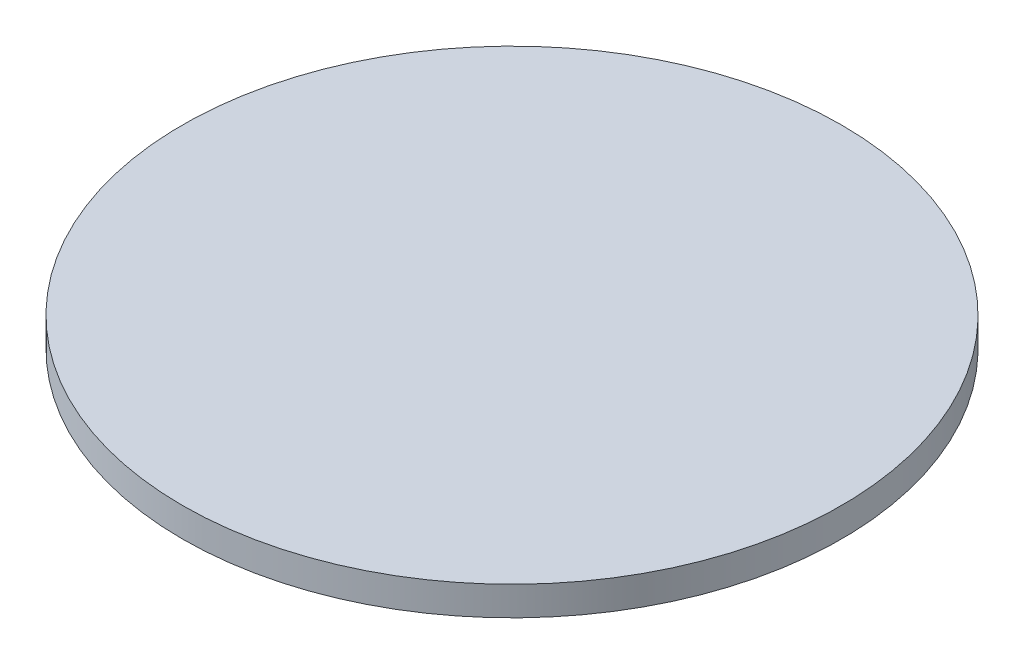
SolidWorks part; units mm, degrees
ref_plane "Front" through (0, 0, 0) normal (0, 0, 1) x (1, 0, 0)
ref_plane "Top" through (0, 0, 0) normal (0, 1, 0) x (1, 0, 0)
ref_plane "Right" through (0, 0, 0) normal (1, 0, 0) x (0, 0, -1)
sketch "Sketch1" plane through (0, 0, 0) normal (0, 1, 0) x (1, 0, 0)
  circle A0 centre (0, 0) radius 6.35
  dimension "D1" = 12.7
extrude "Boss-Extrude1" add sketch "Sketch1" along normal blind 0.5605
